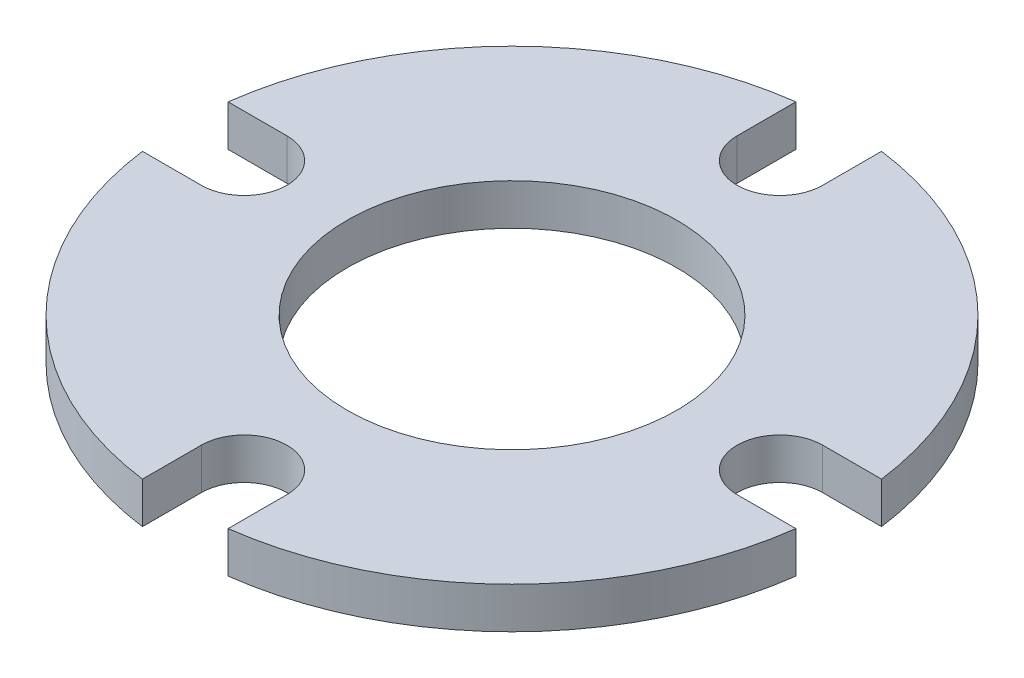
SolidWorks part; units mm, degrees
ref_plane "Front Plane" through (0, 0, 0) normal (0, 0, 1) x (1, 0, 0)
ref_plane "Top Plane" through (0, 0, 0) normal (0, 1, 0) x (1, 0, 0)
ref_plane "Right Plane" through (0, 0, 0) normal (1, 0, 0) x (0, 0, -1)
sketch "Sketch2" plane through (0, 0, 0) normal (0, 1, 0) x (1, 0, 0)
  line L0 (20.6502, 3.302) -> (25.1845, 3.302)
  line L1 (20.6502, -3.302) -> (25.1845, -3.302)
  line L2 (3.302, -20.6502) -> (3.302, -25.1845)
  line L3 (-3.302, -20.6502) -> (-3.302, -25.1845)
  line L4 (-20.6502, -3.302) -> (-25.1845, -3.302)
  line L5 (-20.6502, 3.302) -> (-25.1845, 3.302)
  line L6 (-3.302, 20.6502) -> (-3.302, 25.1845)
  line L7 (3.302, 20.6502) -> (3.302, 25.1845)
  arc A0 (25.1845, 3.302) -> (3.302, 25.1845) centre (0, 0) ccw
  arc A1 (20.6502, 3.302) -> (20.6502, -3.302) centre (20.6502, 0) ccw
  arc A2 (3.302, -20.6502) -> (-3.302, -20.6502) centre (0, -20.6502) ccw
  arc A3 (-20.6502, -3.302) -> (-20.6502, 3.302) centre (-20.6502, 0) ccw
  arc A4 (-3.302, 20.6502) -> (3.302, 20.6502) centre (0, 20.6502) ccw
  arc A5 (-3.302, 25.1845) -> (-25.1845, 3.302) centre (0, 0) ccw
  arc A6 (-25.1845, -3.302) -> (-3.302, -25.1845) centre (0, 0) ccw
  arc A7 (3.302, -25.1845) -> (25.1845, -3.302) centre (0, 0) ccw
  point P1 (-19.9062, 11.3923)
  point P5 (0, 0)
  point P25 (0, 0)
  dimension "D1" = 50.8
  dimension "D3" = 6.604
  dimension "D2" = 20.6502
  dimension "D4" = 4
extrude "Boss-Extrude1" add sketch "Sketch2" along normal mid plane 3.175
hole_wizard "Hole1" positions "Sketch3" profile "Sketch4" legacy end condition through all
sketch "Sketch3" plane through (0, 1.5875, 0) normal (0, 1, 0) x (1, 0, 0)
  point P0 (0, 0)
sketch "Sketch4" plane through (0, 1.5875, 0) normal (1, 0, 0) x (0, 0, 1)
  line L0 (0, 0) -> (0, 3.175)
  line L1 (0, 3.175) -> (12.7, 3.175)
  line L2 (12.7, 3.175) -> (12.7, 0)
  line L3 (12.7, 0) -> (0, 0)
  line L4 (0, 110) -> (0, -10) construction
  dimension "Diameter" = 25.4
  dimension "Depth" = 3.175
